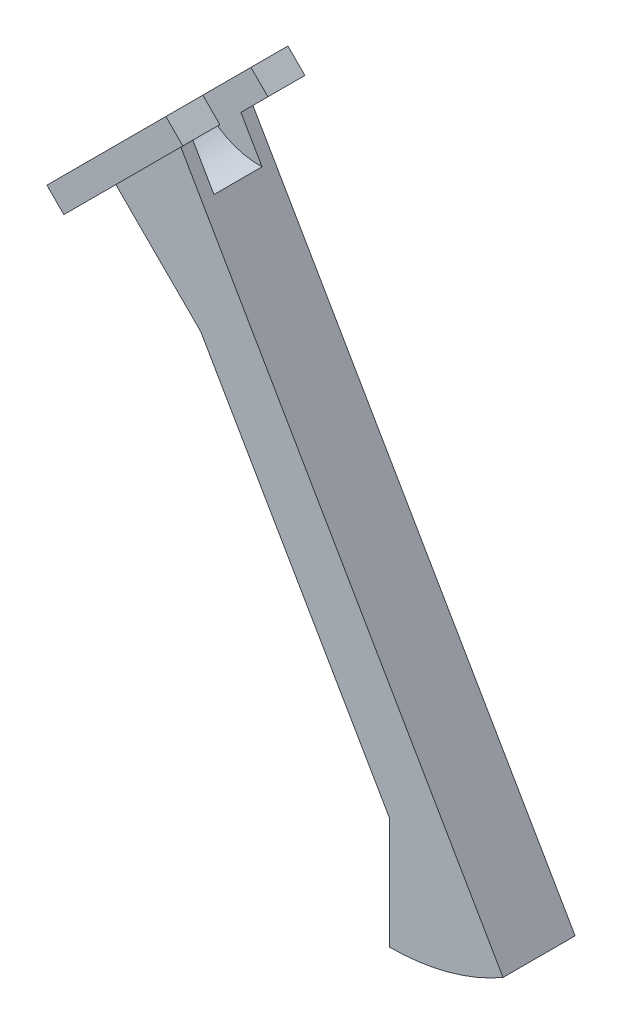
SolidWorks part; units mm, degrees
ref_plane "Front Plane" through (0, 0, 0) normal (0, 0, 1) x (1, 0, 0)
ref_plane "Top Plane" through (0, 0, 0) normal (0, 1, 0) x (1, 0, 0)
ref_plane "Right Plane" through (0, 0, 0) normal (1, 0, 0) x (0, 0, -1)
sketch "Sketch1" plane through (0, 0, 0) normal (0, 0, 1) x (1, 0, 0)
  line L8 (-8.0443, 0) -> (8.0443, 0) construction
  line L9 (0, 0) -> (0, 72.6981) construction
  line L10 (0, 72.6981) -> (-51.4053, 124.1034) construction
  line L13 (-8.0443, 0) -> (-8.0443, 25)
  line L16 (-64.9267, 110.5821) -> (-47.249, 92.9045)
  line L17 (-47.249, 92.9045) -> (-8.0443, 25)
  line L18 (-47.249, 92.9045) -> (-32.8729, 78.5284) construction
  line L19 (16.4557, 6.5648) -> (-51.4053, 124.1034)
  line L23 (-8.0443, 0) -> (16.4557, 6.5648)
  line L24 (-51.4053, 124.1034) -> (-64.9267, 110.5821)
  line L25 (-58.166, 117.3428) -> (4.2057, 3.2824) construction
  point P3 (0, 0)
  dimension "D1" = 135
  dimension "D2" = 130
  dimension "D3" = 15
  dimension "D6" = 12
  dimension "D7" = 15
  dimension "D9" = 25
  dimension "D10" = 25
extrude "tibia_raw" add sketch "Sketch1" along normal mid plane 15
sketch "Sketch4" plane through (0, 0, 0) normal (0, 0, 1) x (1, 0, 0)
  line L0 (16.4557, 6.5648) -> (-51.4053, 124.1034) construction
  line L2 (-8.0443, 0) -> (16.4557, 6.5648) construction
  line L3 (-8.0443, 0) -> (-8.0443, 25) construction
  line L4 (-8.0443, 1.6696) -> (-8.0443, 0)
  line L5 (-8.0443, 0) -> (16.4557, 6.5648)
  line L6 (16.4557, 6.5648) -> (15.6208, 8.0107)
  line L8 (-47.249, 92.9045) -> (-8.0443, 25) construction
  arc A1 (-8.0443, 1.6696) -> (15.6208, 8.0107) centre (-8.0443, 49) ccw
  point P6 (-27.6467, 58.9522)
  point P8 (0, 0)
  point P12 (-27.8537, 61.5934)
  point P16 (-27.8537, 61.5934)
  point P17 (0, 0)
  point P18 (0, 0)
  point P22 (-21.7915, 65.0934)
  point P23 (-21.7915, 65.0934)
  point P24 (-12.5, 1.7732)
extrude "arrondissement_patte" cut sketch "Sketch4" against normal through all both and the other way through all contours A1 L4 L5 | A1 L5 L6
sketch "Sketch10" plane through (-87.7544, 87.7544, 0) normal (-0.7071, 0.7071, 0) x (0, 0, 1)
  line L0 (7.5, 51.4053) -> (-7.5, 51.4053) construction
  line L1 (-12.7, 24.3443) -> (12.7, 24.3443)
  line L2 (-12.7, 24.3443) -> (-12.7, 59.3443)
  line L3 (-12.7, 59.3443) -> (12.7, 59.3443)
  line L4 (12.7, 24.3443) -> (12.7, 59.3443)
  line L5 (-12.7, 24.3443) -> (12.7, 59.3443) construction
  line L6 (-12.7, 59.3443) -> (12.7, 24.3443) construction
  line L7 (-7.5, 51.4053) -> (-7.5, 32.2833) construction
  point P0 (0, 41.8443)
  point P7 (0, 51.4053)
  point P8 (0, 0)
  point P11 (-7.5, 41.8443)
  dimension "D1" = 25.4
  dimension "D2" = 35
extrude "Boss-Extrude3" add sketch "Sketch10" along normal blind 5
sketch "Sketch11" plane through (0, 0, 0) normal (0, 0, 1) x (1, 0, 0)
  line L0 (-49.3272, 133.2527) -> (-45.7916, 129.7172) construction
  circle A0 centre (-47.5594, 131.4849) radius 15
  point P4 (-47.5594, 131.4849)
  dimension "D1" = 30
extrude "Cut-Extrude3" cut sketch "Sketch11" against normal mid plane 10 contours A0
hole_wizard "Ø3.0mm Dowel Hole2" positions "Sketch12" profile "Sketch13" hole size "Ø3.0" standard "ANSI Metric" end condition up to next
sketch "Sketch12" plane through (-91.2899, 91.2899, 0) normal (-0.7071, 0.7071, 0) x (0, 0, 1)
  line L0 (-9.525, 55.3143) -> (-9.525, 28.3743) construction
  line L7 (-9.525, 28.3743) -> (9.525, 28.3743) construction
  line L9 (-12.7, 59.3443) -> (-12.7, 24.3443) construction
  line L10 (-12.7, 24.3443) -> (12.7, 24.3443) construction
  line L11 (-12.7, 41.8443) -> (-9.525, 41.8443) construction
  line L14 (0, 28.3743) -> (0, 24.3443) construction
  point P0 (-9.525, 55.3143)
  point P2 (9.525, 55.3143)
  point P4 (9.525, 28.3743)
  point P6 (-9.525, 28.3743)
  dimension "D1" = 26.94
  dimension "D2" = 19.05
sketch "Sketch13" plane through (-52.1768, 130.403, -9.525) normal (0, 0, 1) x (-0.7071, -0.7071, 0)
  line L0 (0, 0) -> (0, 5)
  line L1 (0, 5) -> (1.5, 5)
  line L2 (1.5, 5) -> (1.5, 0.025)
  line L3 (1.5, 0.025) -> (1.525, 0)
  line L5 (1.525, 0) -> (0, 0)
  line L6 (-1.5, 0.025) -> (-1.525, 0) construction
  line L11 (0, -6.35) -> (0, 107.95) construction
  dimension "Thru Hole Dia." = 3
  dimension "Thru Hole Depth" = 5
  dimension "Near C'Sink Dia." = 3.05
  dimension "Near C'Sink Angle" = 90
sketch "Sketch14" plane through (0, 0, 0) normal (0, 0, 1) x (1, 0, 0)
  line L0 (-70.5404, 104.9684) -> (-69.1261, 106.3826) construction
  line L1 (-69.1261, 106.3826) -> (-57.6529, 103.3084)
  line L2 (-64.9267, 110.5821) -> (-47.249, 92.9045) construction
  line L3 (-49.7019, 125.8069) -> (-47.5806, 127.9282) construction
  point P2 (0, 0)
  point P4 (0, 0)
  point P8 (-51.2359, 96.8914)
  dimension "D1" = 120
  dimension "D2" = 2
rib "Rib2" sketch "Sketch14" sketch "Sketch14" thickness 5 extrusion direction parallel to sketch draft on no parameters "D1"=5
